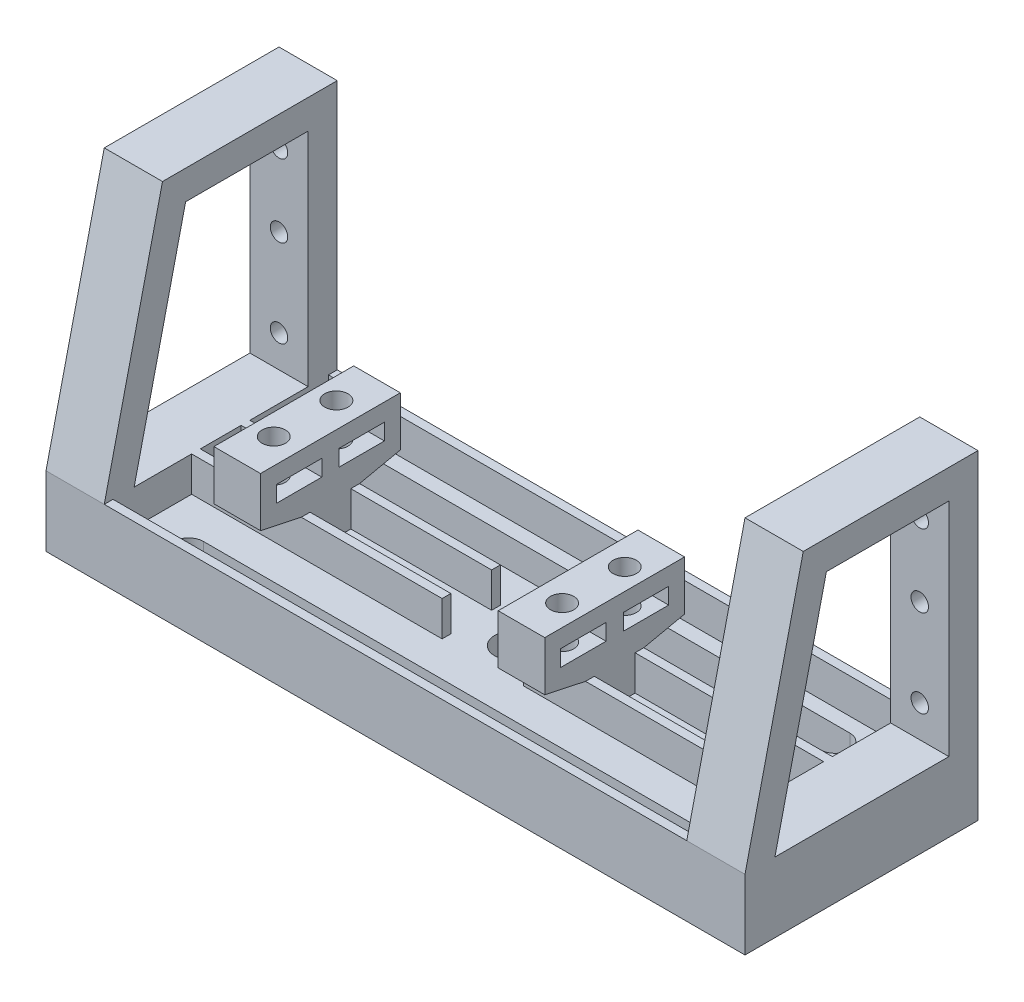
SolidWorks part; units mm, degrees
ref_plane "Front Plane" through (0, 0, 0) normal (0, 0, 1) x (1, 0, 0)
ref_plane "Top Plane" through (0, 0, 0) normal (0, 1, 0) x (1, 0, 0)
ref_plane "Right Plane" through (0, 0, 0) normal (1, 0, 0) x (0, 0, -1)
sketch "Sketch1" plane through (0, 0, 0) normal (1, 0, 0) x (0, 0, -1)
  line L16 (0, 0) -> (40, 0)
  line L17 (40, 0) -> (40, 12)
  line L18 (40, 12) -> (38.5, 12)
  line L19 (38.5, 12) -> (38.5, 6)
  line L20 (38.5, 6) -> (25, 6)
  line L21 (25, 6) -> (25, 12)
  line L22 (25, 12) -> (23.5, 12)
  line L23 (23.5, 12) -> (23.5, 6)
  line L24 (23.5, 6) -> (16.5, 6)
  line L25 (16.5, 6) -> (16.5, 12)
  line L26 (16.5, 12) -> (15, 12)
  line L27 (15, 12) -> (15, 6)
  line L28 (15, 6) -> (1.5, 6)
  line L29 (1.5, 6) -> (1.5, 12)
  line L30 (1.5, 12) -> (0, 12)
  line L31 (0, 12) -> (0, 0)
  dimension "D1" = 40
  dimension "D2" = 1.5
  dimension "D3" = 10
  dimension "D4" = 6
  dimension "D5" = 12
extrude "Boss-Extrude1" add sketch "Sketch1" along normal blind 100
ref_plane "Plane3" through (50, 0, 0) normal (1, 0, 0) x (0, 0, -1)
ref_plane "Plane1" through (18.825, 0, 0) normal (1, 0, 0) x (0, 0, -1)
sketch "Sketch2" plane through (18.825, 0, 0) normal (1, 0, 0) x (0, 0, -1)
  line L0 (15, 6) -> (15, 12)
  line L1 (15, 12) -> (8, 13.5)
  line L2 (8, 13.5) -> (8, 22)
  line L3 (8, 22) -> (32, 22)
  line L4 (32, 22) -> (32, 13.5)
  line L5 (32, 13.5) -> (25, 12)
  line L6 (25, 12) -> (25, 6)
  line L7 (25, 6) -> (15, 6)
  line L8 (23.5, 6) -> (16.5, 6) construction
  line L9 (15, 12) -> (15, 6) construction
  point P0 (20, 6)
  point P9 (20, 6)
  point P22 (20, 22)
  dimension "D1" = 16
  dimension "D2" = 1.5
  dimension "D3" = 24
  dimension "D4" = 6
extrude "Boss-Extrude2" add sketch "Sketch2" against normal blind 8
ref_plane "Plane2" through (59.625, 0, 0) normal (1, 0, 0) x (0, 0, -1)
sketch "Sketch4" plane through (59.625, 0, 0) normal (1, 0, 0) x (0, 0, -1)
  line L0 (25, 6) -> (15, 6) construction
  line L1 (15, 6) -> (15, 12) construction
  line L2 (25, 12) -> (25, 6) construction
  line L3 (32, 22) -> (32, 13.5) construction
  line L4 (32, 13.5) -> (25, 12) construction
  line L5 (15, 12) -> (8, 13.5) construction
  line L6 (8, 13.5) -> (8, 22) construction
  line L7 (8, 22) -> (32, 22) construction
  line L8 (25, 6) -> (15, 6)
  line L9 (15, 6) -> (15, 12)
  line L10 (25, 12) -> (25, 6)
  line L11 (32, 22) -> (32, 13.5)
  line L12 (32, 13.5) -> (25, 12)
  line L13 (15, 12) -> (8, 13.5)
  line L14 (8, 13.5) -> (8, 22)
  line L15 (8, 22) -> (32, 22)
extrude "Boss-Extrude3" add sketch "Sketch4" along normal blind 8
sketch "Sketch10" plane through (0, 22, 0) normal (0, 1, 0) x (1, 0, 0)
  line L0 (14.475, 14.625) -> (14.475, 25.375) construction
  line L2 (18.825, 32) -> (18.825, 8) construction
  line L3 (59.625, 32) -> (59.625, 8) construction
  circle A0 centre (14.475, 14.625) radius 2
  circle A1 centre (14.475, 25.375) radius 2
  circle A2 centre (63.975, 14.625) radius 2
  circle A3 centre (63.975, 25.375) radius 2
  point P4 (14.475, 16.625)
  point P5 (14.475, 23.375)
  point P6 (16.475, 25.375)
  point P7 (16.475, 14.625)
  point P9 (14.475, 20)
  point P10 (18.825, 20)
  point P17 (65.975, 25.375)
  point P18 (65.975, 14.625)
  dimension "D1" = 4
  dimension "D2" = 10.75
  dimension "D4" = 4.35
  dimension "D5" = 4.35
  dimension "D3" = 2
extrude "Cut-Extrude4" cut sketch "Sketch10" against normal blind 8.75
sketch "Sketch11" plane through (10.825, 0, 0) normal (-1, 0, 0) x (0, 0, 1)
  line L0 (-21.475, 19) -> (-18.525, 19) construction
  line L1 (-29.275, 19) -> (-21.475, 19)
  line L2 (-29.275, 19) -> (-29.275, 16.2)
  line L3 (-29.275, 16.2) -> (-21.475, 16.2)
  line L4 (-21.475, 19) -> (-21.475, 16.2)
  line L5 (-18.525, 19) -> (-10.725, 19)
  line L6 (-18.525, 19) -> (-18.525, 16.2)
  line L7 (-18.525, 16.2) -> (-10.725, 16.2)
  line L8 (-10.725, 19) -> (-10.725, 16.2)
  line L9 (-32, 22) -> (-8, 22) construction
  line L10 (-23.375, 22) -> (-27.375, 22) construction
  point P8 (-20, 22)
  point P9 (-20, 19)
  point P13 (-25.375, 19)
  point P16 (-25.375, 22)
  dimension "D1" = 3
  dimension "D2" = 2.8
  dimension "D3" = 7.8
extrude "Cut-Extrude5" cut sketch "Sketch11" against normal through all
sketch "Sketch5" plane through (0, 0, 0) normal (0, -1, 0) x (1, 0, 0)
  line L0 (8, -31) -> (92, -31)
  line L1 (92, -36) -> (8, -36)
  line L2 (50, -40) -> (50, 0) construction
  line L3 (100, -40) -> (0, -40) construction
  line L4 (100, 0) -> (0, 0) construction
  line L5 (0, -20) -> (100, -20) construction
  line L6 (0, -23.5) -> (0, -16.5) construction
  line L7 (100, -23.5) -> (100, -16.5) construction
  line L8 (92, -4) -> (8, -4)
  line L9 (8, -9) -> (92, -9)
  line L10 (100, -38.5) -> (100, -25) construction
  arc A0 (92, -31) -> (92, -36) centre (92, -33.5) cw
  arc A1 (8, -36) -> (8, -31) centre (8, -33.5) cw
  arc A2 (8, -4) -> (8, -9) centre (8, -6.5) ccw
  arc A3 (92, -9) -> (92, -4) centre (92, -6.5) ccw
  circle A4 centre (50, -20) radius 3
  point P18 (50, -36)
  point P29 (50, -4)
  dimension "D4" = 6
  dimension "D1" = 8
  dimension "D2" = 4
  dimension "D3" = 5
extrude "Cut-Extrude1" cut sketch "Sketch5" against normal up to next
sketch "Sketch6" plane through (0, 6, 0) normal (0, 1, 0) x (1, 0, 0)
  line L0 (59.625, 15) -> (18.825, 15) construction
  line L1 (57, 25) -> (43, 25)
  line L2 (57, 25) -> (57, 15)
  line L3 (57, 15) -> (43, 15)
  line L4 (43, 25) -> (43, 15)
  line L5 (100, 25) -> (0, 25) construction
  line L6 (50, -2.1179) -> (50, 2.1179) construction
  point P7 (50, 15)
  dimension "D1" = 14
extrude "Cut-Extrude2" cut sketch "Sketch6" along normal up to next
sketch "Sketch7" plane through (100, 0, 0) normal (1, 0, 0) x (0, 0, -1)
  line L0 (0, 0) -> (40, 0)
  line L1 (40, 0) -> (40, 12)
  line L2 (40, 12) -> (40, 55)
  line L3 (40, 55) -> (10, 55)
  line L4 (10, 55) -> (0, 12)
  line L5 (0, 12) -> (0, 0)
  line L6 (35, 50) -> (13.9706, 50)
  line L7 (13.9706, 50) -> (5.1334, 12)
  line L9 (35, 12) -> (35, 50)
  line L14 (15, 12) -> (15, 6) construction
  line L15 (13.9706, 50) -> (13.9706, 55) construction
  line L17 (35, 50) -> (40, 50) construction
  line L18 (35, 12) -> (38.5, 12) construction
  line L20 (15, 6) -> (1.5, 6) construction
  line L21 (1.5, 6) -> (1.5, 12) construction
  line L23 (25, 12) -> (25, 6) construction
  line L24 (25, 6) -> (38.5, 6) construction
  line L25 (38.5, 6) -> (38.5, 12) construction
  line L28 (35, 12) -> (5.1334, 12)
  line L30 (5.1334, 12) -> (0.2634, 13.1326) construction
  point P4 (20, 0)
  dimension "D1" = 5
  dimension "D2" = 10
  dimension "D3" = 55
extrude "Boss-Extrude4" add sketch "Sketch7" along normal blind 10
sketch "Sketch8" plane through (0, 0, 0) normal (-1, 0, 0) x (0, 0, 1)
  line L0 (-40, 0) -> (-40, 55) construction
  line L1 (-40, 55) -> (-10, 55) construction
  line L2 (-35, 50) -> (-13.9706, 50) construction
  line L3 (-35, 12) -> (-35, 50) construction
  line L4 (-13.9706, 50) -> (-5.1334, 12) construction
  line L5 (-5.1334, 12) -> (-35, 12) construction
  line L6 (-10, 55) -> (0, 12) construction
  line L7 (0, 12) -> (0, 0) construction
  line L8 (0, 0) -> (-40, 0) construction
  line L9 (-40, 0) -> (-40, 55)
  line L10 (-40, 55) -> (-10, 55)
  line L11 (-35, 50) -> (-13.9706, 50)
  line L12 (-35, 12) -> (-35, 50)
  line L13 (-13.9706, 50) -> (-5.1334, 12)
  line L56 (-5.1334, 12) -> (-35, 12)
  line L57 (-10, 55) -> (0, 12)
  line L58 (0, 12) -> (0, 0)
  line L59 (0, 0) -> (-40, 0)
extrude "Boss-Extrude11" add sketch "Sketch8" along normal blind 10
sketch "Sketch9" plane through (0, 0, -40) normal (0, 0, -1) x (-1, 0, 0)
  line L0 (-110, 55) -> (-100, 55) construction
  line L2 (10, 55) -> (0, 55) construction
  circle A0 centre (-105, 45) radius 1.5
  circle A1 centre (-105, 32.5) radius 1.5
  circle A2 centre (-105, 17.5) radius 1.5
  circle A3 centre (5, 45) radius 1.5
  circle A4 centre (5, 32.5) radius 1.5
  circle A5 centre (5, 17.5) radius 1.5
  point P6 (-105, 55)
  point P9 (-105, 55)
  point P12 (5, 55)
  dimension "D1" = 3
  dimension "D2" = 10
  dimension "D3" = 12.5
  dimension "D4" = 37.5
  dimension "D5" = 2
extrude "Cut-Extrude3" cut sketch "Sketch9" against normal up to next
